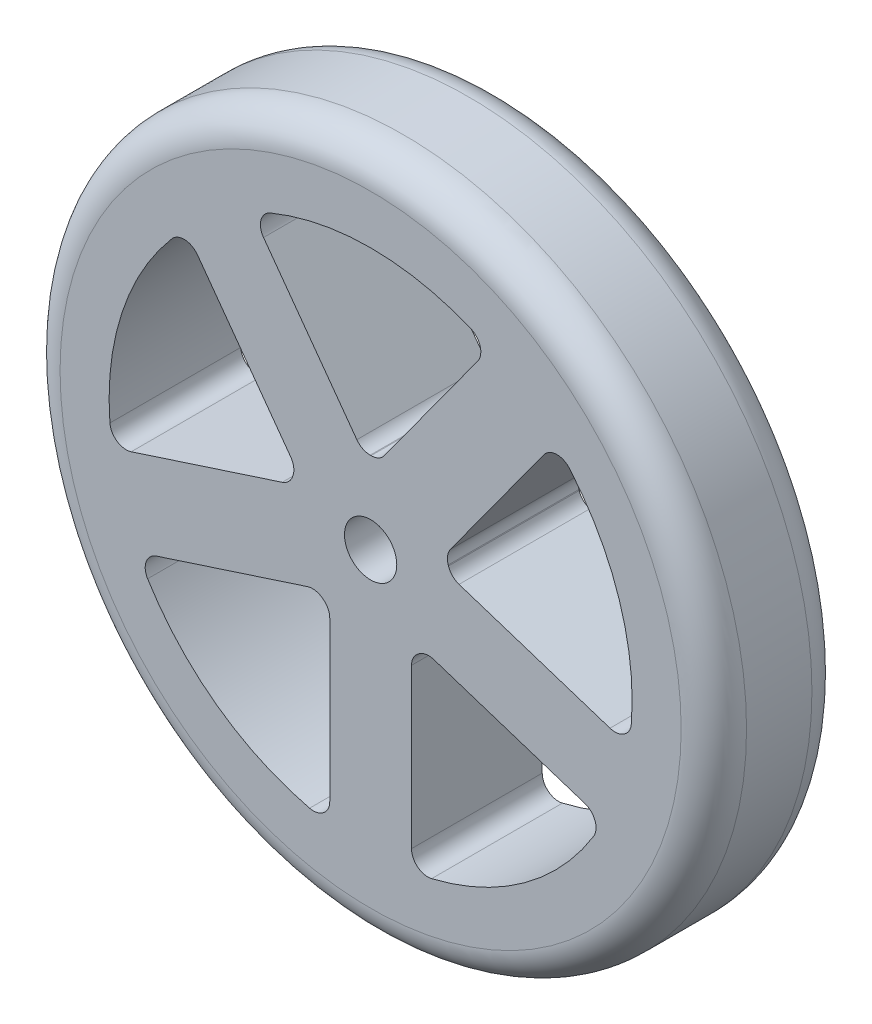
SolidWorks part; units mm, degrees
ref_plane "Plan de face" through (0, 0, 0) normal (0, 0, 1) x (1, 0, 0)
ref_plane "Plan de dessus" through (0, 0, 0) normal (0, 1, 0) x (1, 0, 0)
ref_plane "Plan de droite" through (0, 0, 0) normal (1, 0, 0) x (0, 0, -1)
sketch "Esquisse1" plane through (0, 0, 0) normal (0, 0, 1) x (1, 0, 0)
  circle A0 centre (0, 0) radius 105
  dimension "D1" = 210
extrude "Boss.-Extru.1" add sketch "Esquisse1" along normal blind 40
sketch "Esquisse2" plane through (0, 0, 40) normal (0, 0, 1) x (1, 0, 0)
  line L0 (0, 0) -> (0, 80) construction
  line L1 (2.6132, 24.863) -> (36.3326, 71.2737)
  line L2 (-2.6132, 24.863) -> (-36.3326, 71.2737)
  line L3 (24.4537, 5.1978) -> (79.0127, -12.5295)
  line L4 (22.8386, 10.1684) -> (56.558, 56.5791)
  line L5 (12.5, -21.6506) -> (12.5, -79.0174)
  line L6 (16.7283, -18.5786) -> (71.2873, -36.3059)
  line L7 (-16.7283, -18.5786) -> (-71.2873, -36.3059)
  line L8 (-12.5, -21.6506) -> (-12.5, -79.0174)
  line L9 (-22.8386, 10.1684) -> (-56.558, 56.5791)
  line L10 (-24.4537, 5.1978) -> (-79.0127, -12.5295)
  arc A0 (-36.3326, 71.2737) -> (36.3326, 71.2737) centre (0, 0) cw
  arc A1 (-2.6132, 24.863) -> (2.6132, 24.863) centre (0, 0) cw
  arc A2 (22.8386, 10.1684) -> (24.4537, 5.1978) centre (0, 0) cw
  arc A3 (56.558, 56.5791) -> (79.0127, -12.5295) centre (0, 0) cw
  arc A4 (16.7283, -18.5786) -> (12.5, -21.6506) centre (0, 0) cw
  arc A5 (71.2873, -36.3059) -> (12.5, -79.0174) centre (0, 0) cw
  arc A6 (-12.5, -21.6506) -> (-16.7283, -18.5786) centre (0, 0) cw
  arc A7 (-12.5, -79.0174) -> (-71.2873, -36.3059) centre (0, 0) cw
  arc A8 (-24.4537, 5.1978) -> (-22.8386, 10.1684) centre (0, 0) cw
  arc A9 (-79.0127, -12.5295) -> (-56.558, 56.5791) centre (0, 0) cw
  circle A10 centre (0, 0) radius 105 construction
  point P25 (0, 0)
  dimension "D1" = 25
  dimension "D2" = 25
  dimension "D4" = 25
  dimension "D3" = 5
extrude "Enlèv. mat.-Extru.1" cut sketch "Esquisse2" against normal through all both and the other way through all
sketch "Esquisse3" plane through (0, 0, 40) normal (0, 0, 1) x (1, 0, 0)
  circle A0 centre (0, 0) radius 8
  dimension "D1" = 16
extrude "Enlèv. mat.-Extru.2" cut sketch "Esquisse3" against normal through all both and the other way through all
fillet "Congé1" radius 5 20 edges at (-24.4537, 5.1978, 20) (-22.8386, 10.1684, 20) (-2.6132, 24.863, 20) (2.6132, 24.863, 20) (22.8386, 10.1684, 20) (24.4537, 5.1978, 20) (16.7283, -18.5786, 20) (12.5, -21.6506, 20) (-12.5, -21.6506, 20) (-16.7283, -18.5786, 20) (71.2873, -36.3059, 20) (12.5, -79.0174, 20) (-71.2873, -36.3059, 20) (-12.5, -79.0174, 20) (-79.0127, -12.5295, 20) (-56.558, 56.5791, 20) (-36.3326, 71.2737, 20) (36.3326, 71.2737, 20) (56.558, 56.5791, 20) (79.0127, -12.5295, 20)
fillet "Congé2" radius 10 2 edges at (105, 0, 0) (105, 0, 40)
